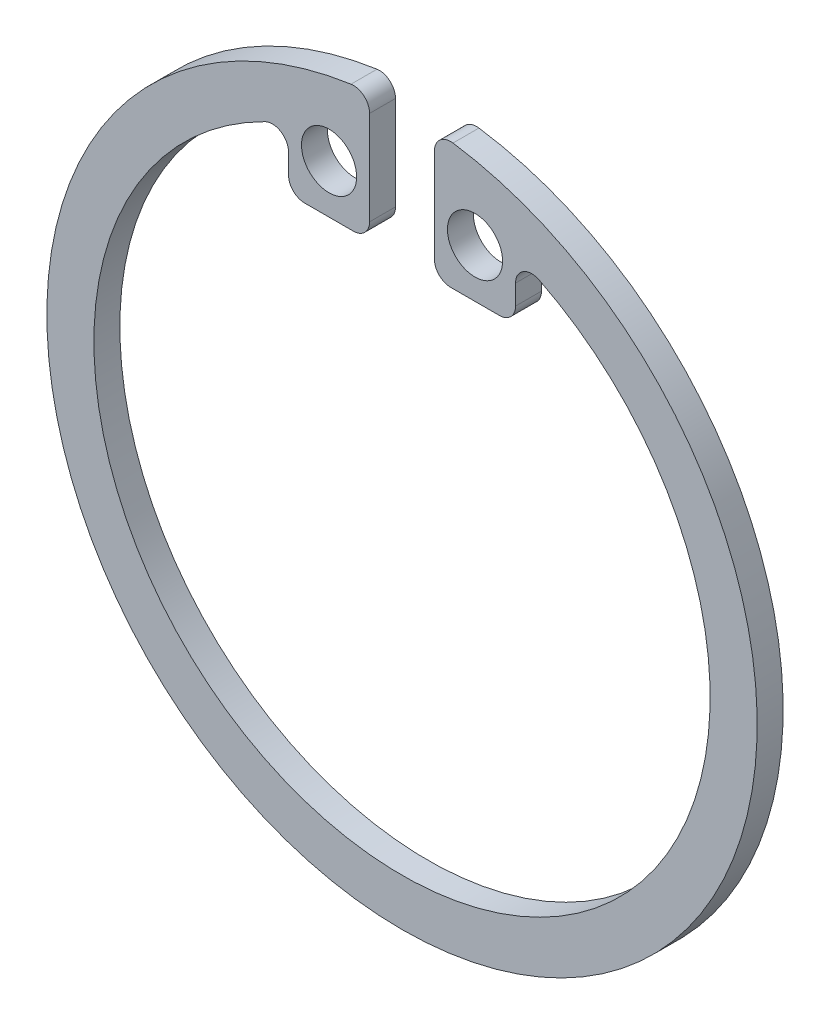
SolidWorks part; units mm, degrees
ref_plane "Front Plane" through (0, 0, 0) normal (0, 0, 1) x (1, 0, 0)
ref_plane "Top Plane" through (0, 0, 0) normal (0, 1, 0) x (1, 0, 0)
ref_plane "Right Plane" through (0, 0, 0) normal (1, 0, 0) x (0, 0, -1)
sketch "Sketch1" plane through (0, 0, 0) normal (0, 0, 1) x (1, 0, 0)
  circle A0 centre (0, 0) radius 9.5
  circle A1 centre (0, 0) radius 10.95
  dimension "D1" = 19
  dimension "D2" = 21.9
extrude "Boss-Extrude1" add sketch "Sketch1" along normal blind 0.8
sketch "Sketch2" plane through (0, 0, 0.8) normal (0, 0, 1) x (1, 0, 0)
  line L0 (0, 0) -> (0, 14.789)
  line L1 (1, 0) -> (1, 14.789)
  line L2 (-1, 0) -> (-1, 14.789)
  line L3 (1, 0) -> (-1, 0)
  line L4 (1, 14.789) -> (-1, 14.789)
  dimension "D1" = 1
  dimension "D2" = 1
extrude "Cut-Extrude1" cut sketch "Sketch2" against normal through all contours L1 L4 L2 L3
sketch "Sketch3" plane through (0, 0, 0.8) normal (0, 0, 1) x (1, 0, 0)
  line L1 (1, 9.4472) -> (3.5, 9.4472)
  line L2 (1, 9.4472) -> (1, 6.9472)
  line L3 (1, 6.9472) -> (3.5, 6.9472)
  line L4 (3.5, 9.4472) -> (3.5, 6.9472)
  line L5 (-1, 9.4472) -> (-3.5, 9.4472)
  line L6 (-1, 9.4472) -> (-1, 6.9472)
  line L7 (-1, 6.9472) -> (-3.5, 6.9472)
  line L8 (-3.5, 9.4472) -> (-3.5, 6.9472)
  dimension "D1" = 2.5
  dimension "D2" = 2.5
  dimension "D3" = 2.5
  dimension "D4" = 2.5
extrude "Boss-Extrude2" add sketch "Sketch3" against normal up to surface (0.8 mm away) up to face at (0, -0.0246, 0)
fillet "Fillet1" radius 0.5 4 edges at (-3.5, 8.8318, 0.4) (3.5, 8.8318, 0.4) (1, 10.9042, 0.4) (-1, 10.9042, 0.4)
fillet "Fillet2" radius 0.5 4 edges at (3.5, 6.9472, 0.4) (1, 6.9472, 0.4) (-1, 6.9472, 0.4) (-3.5, 6.9472, 0.4)
sketch "Sketch4" plane through (0, 0, 0.8) normal (0, 0, 1) x (1, 0, 0)
  line L0 (-3, 6.9472) -> (-1.5, 6.9472) construction
  line L1 (1.5, 6.9472) -> (3, 6.9472) construction
  circle A0 centre (2.25, 8.4472) radius 0.85
  circle A1 centre (-2.25, 8.4472) radius 0.85
  point P7 (-2.25, 6.9472)
  point P11 (2.25, 6.9472)
  dimension "D1" = 1.5
  dimension "D3" = 1.7
  dimension "D4" = 1.7
  dimension "D2" = 1.5
extrude "Cut-Extrude2" cut sketch "Sketch4" against normal through all
